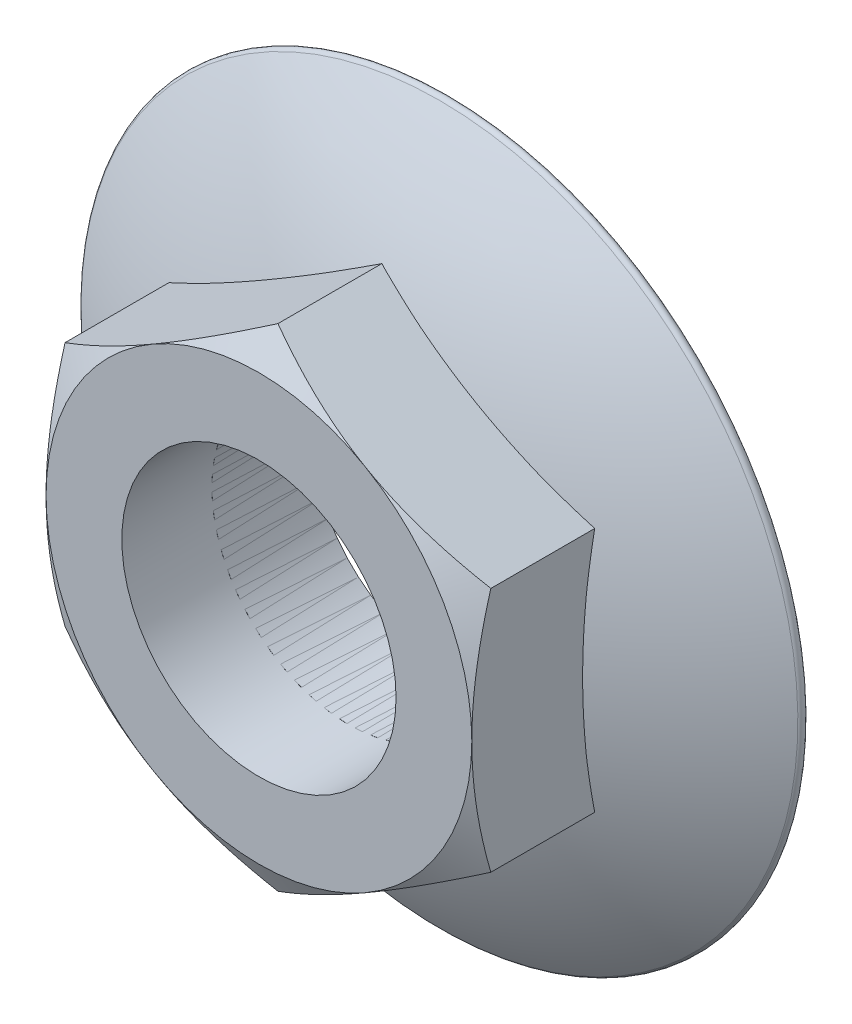
SolidWorks part; units mm, degrees
ref_plane "Front Plane" through (0, 0, 0) normal (0, 0, 1) x (1, 0, 0)
ref_plane "Top Plane" through (0, 0, 0) normal (0, 1, 0) x (1, 0, 0)
ref_plane "Right Plane" through (0, 0, 0) normal (1, 0, 0) x (0, 0, -1)
sketch "Sketch1" plane through (0, 0, 0) normal (0, 0, 1) x (1, 0, 0)
  line L1 (22.5, -12.9904) -> (22.5, 12.9904)
  line L2 (22.5, 12.9904) -> (0, 25.9808)
  line L3 (0, 25.9808) -> (-22.5, 12.9904)
  line L4 (-22.5, 12.9904) -> (-22.5, -12.9904)
  line L5 (-22.5, -12.9904) -> (0, -25.9808)
  line L6 (0, -25.9808) -> (22.5, -12.9904)
  circle A0 centre (0, 0) radius 22.5 construction
  dimension "D1" = 45
extrude "Boss-Extrude1" add sketch "Sketch1" along normal blind 20
sketch "Sketch2" plane through (0, 0, 0) normal (1, 0, 0) x (0, 0, -1)
  line L0 (0, 0) -> (-12, 0)
  line L1 (0, -37.6135) -> (0, 0)
  arc A0 (-12, 0) -> (-0.9212, -37.8829) centre (58.3078, 0) ccw
  arc A1 (-0.9212, -37.8829) -> (0, -37.6135) centre (-0.5, -37.6135) ccw
  dimension "D2" = 0.5
  dimension "D1" = 12
revolve "Revolve2" add sketch "Sketch2" angle 360 about L0
sketch "Sketch3" plane through (0, 0, 20) normal (0, 0, 1) x (1, 0, 0)
  circle A0 centre (0, 0) radius 22.5
extrude "Cut-Extrude1" cut sketch "Sketch3" against normal blind 20 draft 60 flip side to cut
sketch "Sketch4" plane through (0, 0, 20) normal (0, 0, 1) x (1, 0, 0)
  circle A0 centre (0, 0) radius 14.4939
extrude "Cut-Extrude3" cut sketch "Sketch4" against normal through all
cosmetic thread "Cosmetic Thread2" parameters "D2"=31.75
